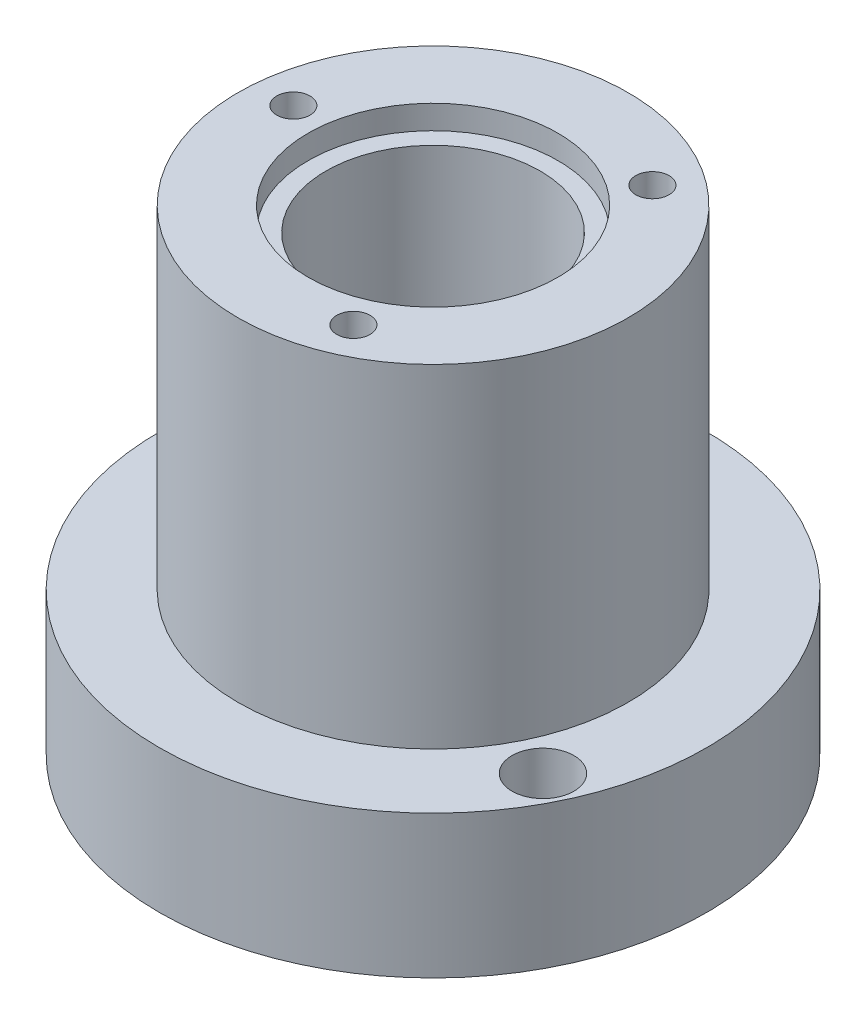
SolidWorks part; units mm, degrees
material "Copper"
ref_plane "Front Plane" through (0, 0, 0) normal (0, 0, 1) x (1, 0, 0)
ref_plane "Top Plane" through (0, 0, 0) normal (0, 1, 0) x (1, 0, 0)
ref_plane "Right Plane" through (0, 0, 0) normal (1, 0, 0) x (0, 0, -1)
sketch "Sketch1" plane through (0, 0, 0) normal (0, 1, 0) x (1, 0, 0)
  circle A0 centre (13.0282, -14.383) radius 14.605
  dimension "D1" = 29.21
extrude "Boss-Extrude2" add sketch "Sketch1" along normal blind 25.4 contours A0
ref_point "Point2"
sketch "Sketch10" plane through (0, 25.4, 0) normal (0, 1, 0) x (1, 0, 0)
  circle A0 centre (13.0282, -14.383) radius 5.715
  dimension "D1" = 11.43
extrude "Cut-Extrude5" cut sketch "Sketch10" against normal through all
sketch "Sketch11" plane through (0, 25.4, 0) normal (0, 1, 0) x (1, 0, 0)
  circle A0 centre (13.0282, -14.383) radius 6.6675
  dimension "D1" = 13.335
extrude "Cut-Extrude6" cut sketch "Sketch11" against normal blind 1.27
sketch "Sketch12" plane through (0, 25.4, 0) normal (0, 1, 0) x (1, 0, 0)
  circle A0 centre (13.0282, -14.383) radius 10.414
  dimension "D1" = 20.828
extrude "Cut-Extrude7" cut sketch "Sketch12" against normal blind 17.78 flip side to cut
sketch "Sketch13" plane through (0, 25.4, 0) normal (0, 1, 0) x (1, 0, 0)
  line L0 (13.0282, -14.383) -> (4.6924, -13.5041)
  dimension "D1" = 8.382
hole_wizard "#50 (0.07) Diameter Hole1" positions "Sketch16" profile "Sketch17" hole size "#50" standard "ANSI Inch"
sketch "Sketch16" plane through (0, 25.4, 0) normal (0, 1, 0) x (1, 0, 0)
  point P0 (4.6924, -13.5041)
sketch "Sketch17" plane through (4.6924, 25.4, 13.5041) normal (1, 0, 0) x (0, 0, 1)
  line L0 (0, 0) -> (0, 3.0742)
  line L1 (0, 3.0742) -> (0.889, 2.54)
  line L2 (0.889, 2.54) -> (0.889, 0)
  line L5 (0.889, 0) -> (0, 0)
  line L10 (0, 3.0742) -> (-0.889, 2.54) construction
  line L11 (0, -6.35) -> (0, 107.95) construction
  dimension "Hole Dia." = 1.778
  dimension "Hole Depth" = 2.54
  dimension "Drill Angle" = 118
pattern_circular "CirPattern1" count 3 over 360 about axis through (13.0282, 0, 14.383) along (0, 1, 0) of "#50 (0.07) Diameter Hole1"
sketch "Sketch18" plane through (0, 0, 0) normal (0, -1, 0) x (-1, 0, 0)
  line L0 (-13.0282, -14.383) -> (-8.1633, -24.3882)
  line L1 (-13.0282, -14.383) -> (-1.6068, -8.8295)
  dimension "D1" = 11.1252
  dimension "D2" = 12.7
hole_wizard "1/16 (0.0625) Diameter Hole2" positions "Sketch23" profile "Sketch24" hole size "1/16" standard "ANSI Inch"
sketch "Sketch23" plane through (0, 0, 0) normal (0, -1, 0) x (-1, 0, 0)
  point P0 (-8.1633, -24.3882)
sketch "Sketch24" plane through (8.1633, 0, 24.3882) normal (1, 0, 0) x (0, 0, -1)
  line L0 (0, 0) -> (0, 4.4774)
  line L1 (0, 4.4774) -> (0.7937, 4.0005)
  line L2 (0.7937, 4.0005) -> (0.7937, 0)
  line L5 (0.7937, 0) -> (0, 0)
  line L10 (0, 4.4774) -> (-0.7938, 4.0005) construction
  line L11 (0, -6.35) -> (0, 107.95) construction
  dimension "Hole Dia." = 1.5875
  dimension "Hole Depth" = 4.0005
  dimension "Drill Angle" = 118
pattern_circular "CirPattern2" count 2 every 180 about axis through (13.0282, 0, 14.383) along (0, 1, 0) of "1/16 (0.0625) Diameter Hole2"
sketch "Sketch26" plane through (0, 0, 0) normal (0, -1, 0) x (-1, 0, 0)
  circle A0 centre (-1.6068, -8.8295) radius 1.651
  dimension "D1" = 3.302
extrude "Cut-Extrude8" cut sketch "Sketch26" against normal blind 8.89
pattern_circular "CirPattern3" count 2 every 180 about axis through (13.0282, 0, 14.383) along (0, 1, 0) of "Cut-Extrude8"
sketch "Sketch27" plane through (0, 0, 0) normal (0, -1, 0) x (-1, 0, 0)
  circle A0 centre (-5.8274, -17.1427) radius 0.7938
  dimension "D1" = 1.5875
extrude "Cut-Extrude9" cut sketch "Sketch27" against normal blind 24.13 contours A0
sketch "Sketch30" plane through (0, 0, 0) normal (0, -1, 0) x (-1, 0, 0)
  line L0 (-5.8274, -17.1427) -> (-5.8274, -15.2377)
  line L1 (-5.8274, -17.1427) -> (-5.8274, -19.0477)
  dimension "D1" = 1.905
  dimension "D2" = 1.905
hole_wizard "Tap Drill for #0-80 Tap3" positions "Sketch31" profile "Sketch32" hole size "#0-80" standard "ANSI Inch"
sketch "Sketch31" plane through (0, 0, 0) normal (0, -1, 0) x (-1, 0, 0)
  point P0 (-5.8274, -15.2377)
  point P3 (-5.8274, -19.0477)
sketch "Sketch32" plane through (5.8274, 0, 15.2377) normal (1, 0, 0) x (0, 0, -1)
  line L0 (0, 0) -> (0, 6.8498)
  line L1 (0, 6.8498) -> (0.5956, 6.35)
  line L2 (0.5956, 6.35) -> (0.5956, 0)
  line L5 (0.5956, 0) -> (0, 0)
  line L10 (0, 6.8498) -> (-0.5956, 6.35) construction
  line L11 (0, -6.35) -> (0, 107.95) construction
  dimension "Hole Dia." = 1.1913
  dimension "Hole Depth" = 6.35
  dimension "Drill Angle" = 100
